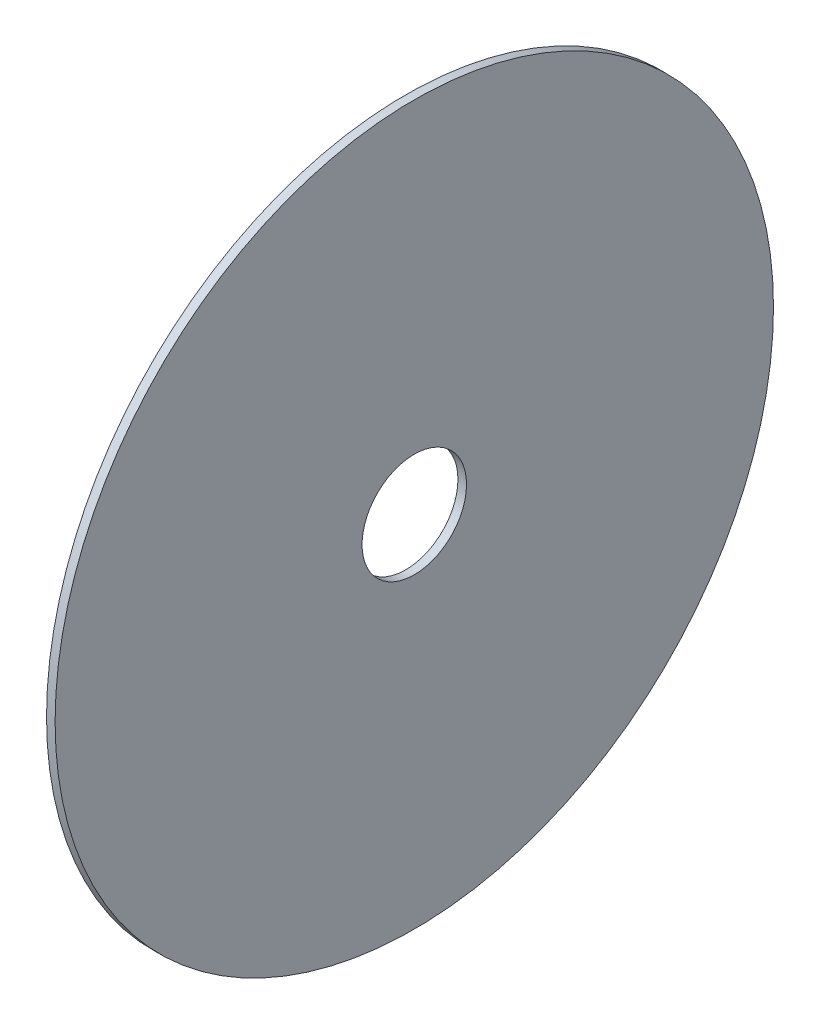
SolidWorks part; units mm, degrees
material "ASTM A36 Steel"
ref_plane "Front Plane" through (0, 0, 0) normal (0, 0, 1) x (1, 0, 0)
ref_plane "Top Plane" through (0, 0, 0) normal (0, 1, 0) x (1, 0, 0)
ref_plane "Right Plane" through (0, 0, 0) normal (1, 0, 0) x (0, 0, -1)
sketch "Sketch1" plane through (0, 0, 0) normal (1, 0, 0) x (0, 0, -1)
  circle A0 centre (0, 0) radius 251
  dimension "D1" = 502
extrude "Boss-Extrude1" add sketch "Sketch1" along normal blind 6
sketch "Sketch2" plane through (6, 0, 0) normal (1, 0, 0) x (0, 0, -1)
  circle A0 centre (0, 0) radius 36.5
  dimension "D1" = 73
extrude "Cut-Extrude1" cut sketch "Sketch2" against normal through all
